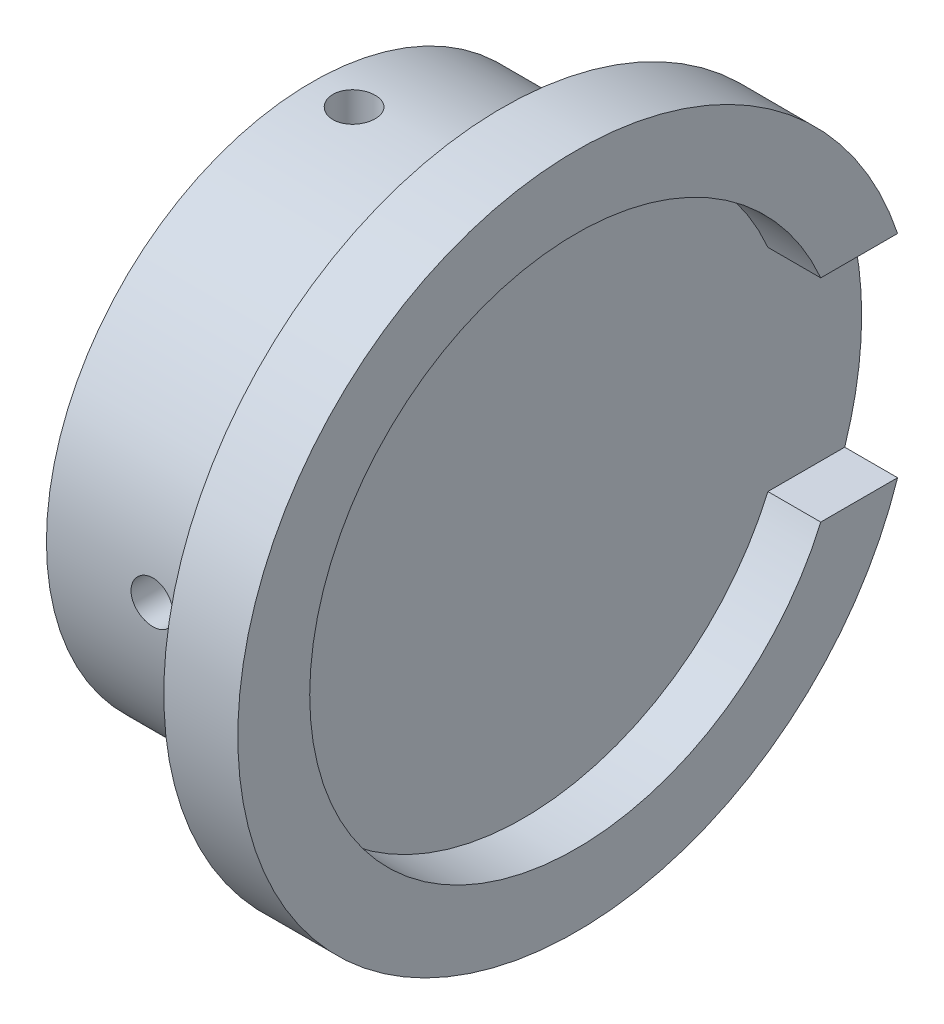
SolidWorks part; units mm, degrees
ref_plane "前视基准面" through (0, 0, 0) normal (0, 0, 1) x (1, 0, 0)
ref_plane "上视基准面" through (0, 0, 0) normal (0, 1, 0) x (1, 0, 0)
ref_plane "右视基准面" through (0, 0, 0) normal (1, 0, 0) x (0, 0, -1)
other "Configuration Table"
sketch "草图1" plane through (0, 0, 0) normal (1, 0, 0) x (0, 0, -1)
  circle A0 centre (0, 0) radius 12.55
  dimension "D1" = 25.1
extrude "凸台-拉伸1" add sketch "草图1" along normal blind 10
sketch "草图2" plane through (0, 0, 0) normal (-1, 0, 0) x (0, 0, 1)
  circle A0 centre (0, 0) radius 3
  dimension "D1" = 6
extrude "切除-拉伸1" cut sketch "草图2" against normal blind 7
sketch "草图3" plane through (0, 0, 0) normal (0, 1, 0) x (1, 0, 0)
  line L0 (0, 12.55) -> (0, -12.55) construction
  circle A0 centre (2, 0) radius 1
  dimension "D1" = 2
  dimension "D2" = 2
extrude "切除-拉伸2" cut sketch "草图3" against normal up to next and the other way up to next
sketch "草图4" plane through (0, 0, 0) normal (0, 0, 1) x (1, 0, 0)
  line L1 (0, 12.55) -> (0, -12.55) construction
  circle A0 centre (5, 0) radius 1
  dimension "D2" = 2
  dimension "D1" = 5
extrude "切除-拉伸3" cut sketch "草图4" against normal blind 19 and the other way blind 21
sketch "草图5" plane through (10, 0, 0) normal (1, 0, 0) x (0, 0, -1)
  circle A0 centre (0, 0) radius 16
  dimension "D1" = 32
extrude "凸台-拉伸2" add sketch "草图5" along normal blind 2.5 and the other way blind 1
sketch "草图6" plane through (12.5, 0, 0) normal (1, 0, 0) x (0, 0, -1)
  circle A0 centre (0, 0) radius 12.6
  dimension "D1" = 25.2
extrude "切除-拉伸4" cut sketch "草图6" against normal blind 2.5
fillet "圆角1" radius 2 1 edges at (9, 0, -12.55)
sketch "草图7" plane through (0, 0, 0) normal (0, 0, 1) x (1, 0, 0)
  line L0 (0, 0) -> (12.5, 0) construction
  line L7 (0, 12.55) -> (0, -12.55) construction
  line L8 (12.5, -16) -> (12.5, 16) construction
  line L10 (12.5, 5) -> (10, 5)
  line L11 (12.5, 5) -> (12.5, -5)
  line L12 (12.5, -5) -> (10, -5)
  line L13 (10, 5) -> (10, -5)
  dimension "D1" = 2.5
  dimension "D2" = 10
  dimension "D3" = 5
extrude "切除-拉伸5" cut sketch "草图7" against normal blind 21.5
